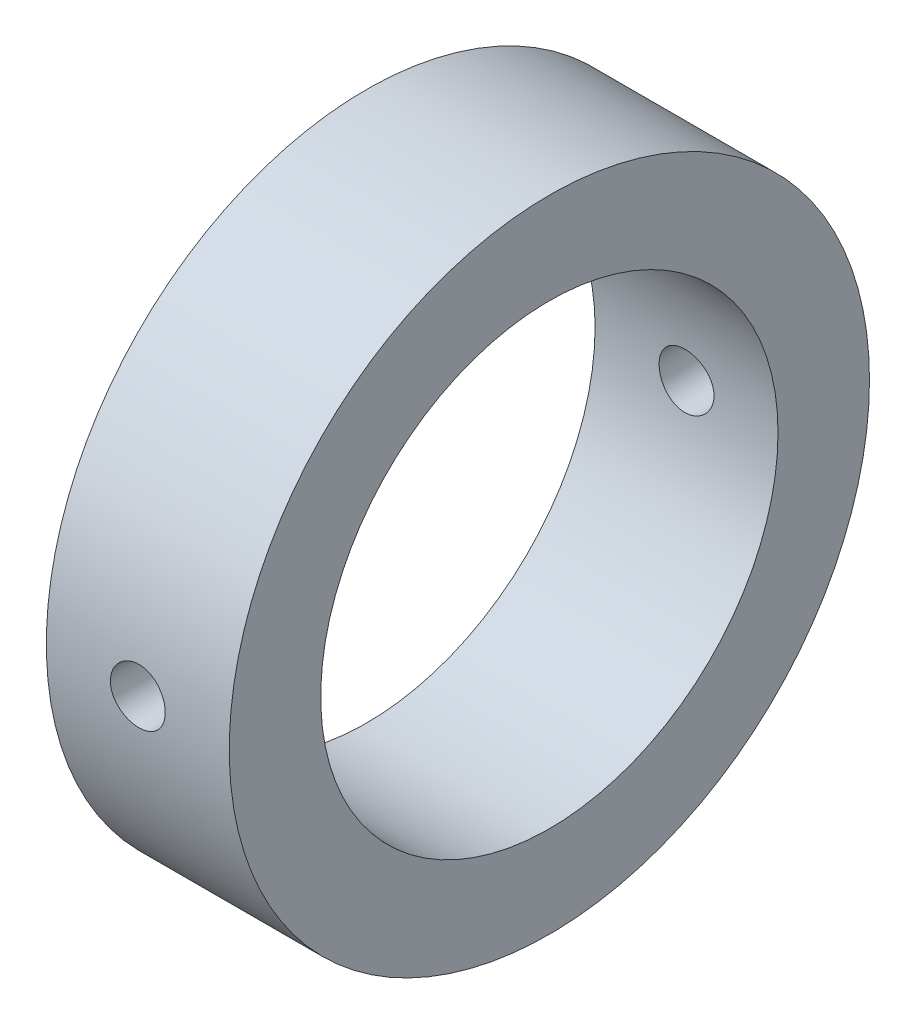
SolidWorks part; units mm, degrees
ref_plane "Front Plane" through (0, 0, 0) normal (1, 0, 0) x (0, 1, 0)
ref_plane "Top Plane" through (0, 0, 0) normal (0, 0, 1) x (0, 1, 0)
ref_plane "Right Plane" through (0, 0, 0) normal (0, 1, 0) x (-1, 0, 0)
sketch "Sketch1" plane through (0, 0, 0) normal (1, 0, 0) x (0, 1, 0)
  circle A0 centre (0, 0) radius 35
  circle A1 centre (0, 0) radius 25
  dimension "D1" = 70
  dimension "D2" = 50
extrude "Boss-Extrude1" add sketch "Sketch1" along normal blind 20
sketch "Sketch2" plane through (0, 0, 0) normal (0, 0, 1) x (0, 1, 0)
  circle A0 centre (0, -10) radius 3
  point P2 (0, 0)
  dimension "D1" = 6
  dimension "D2" = 10
extrude "Cut-Extrude1" cut sketch "Sketch2" against normal through all both and the other way through all
